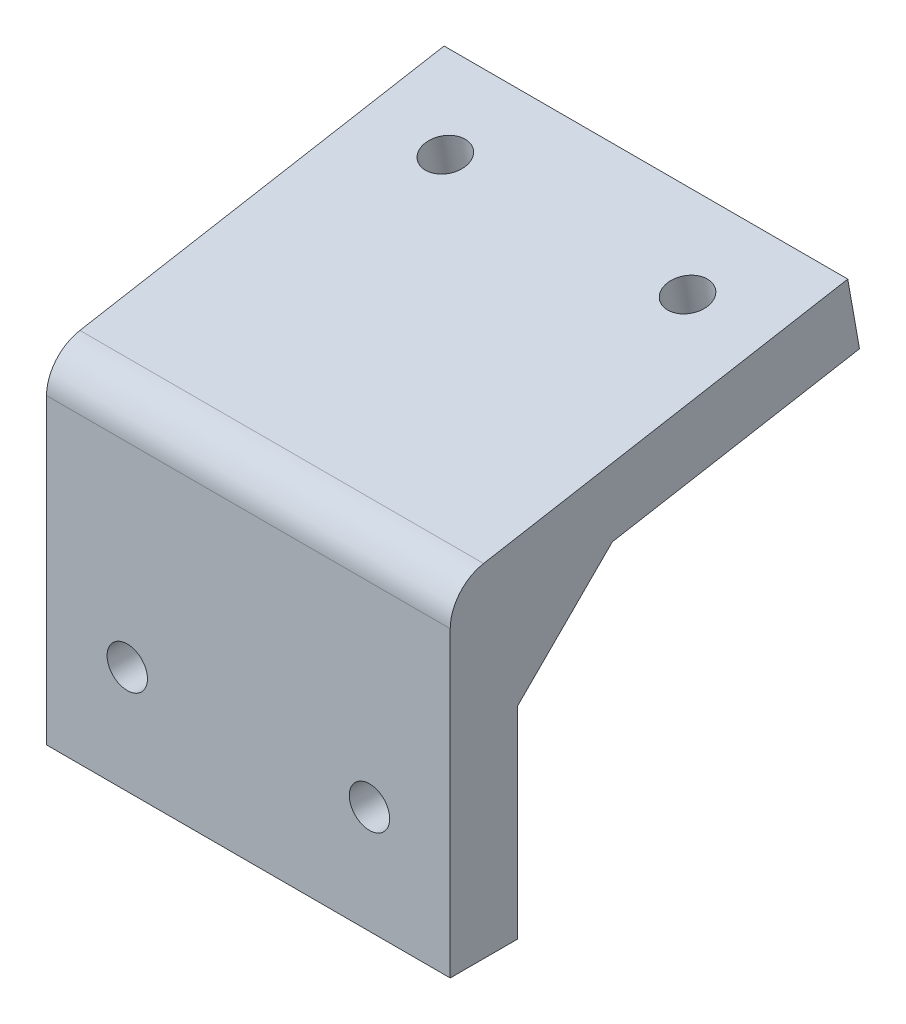
SolidWorks part; units mm, degrees
ref_plane "Front" through (0, 0, 0) normal (0, 0, 1) x (1, 0, 0)
ref_plane "Top" through (0, 0, 0) normal (0, 1, 0) x (1, 0, 0)
ref_plane "Right" through (0, 0, 0) normal (1, 0, 0) x (0, 0, -1)
sketch "草图1" plane through (0, 0, 0) normal (1, 0, 0) x (0, 0, -1)
  line L0 (0, 0) -> (5, 0)
  line L1 (0, 0) -> (0, 25)
  line L2 (0, 25) -> (29.5442, 30.2094)
  line L3 (29.5442, 30.2094) -> (30.4125, 25.2854)
  line L4 (30.4125, 25.2854) -> (5, 20.8045)
  line L5 (5, 20.8045) -> (5, 0)
  dimension "D1" = 5
  dimension "D2" = 25
  dimension "D3" = 30
  dimension "D4" = 5
  dimension "D5" = 100
extrude "凸台-拉伸1" add sketch "草图1" along normal blind 30
fillet "圆角1" radius 3 2 edges at (15, 20.8045, -5) (15, 25, 0)
sketch "草图2" plane through (0, 0, 0) normal (0, 0, 1) x (1, 0, 0)
  line L1 (30, 0) -> (0, 0) construction
  line L2 (0, 22.4827) -> (0, 0) construction
  circle A0 centre (6, 8) radius 1.5
  circle A1 centre (24, 8) radius 1.5
  dimension "D1" = 3
  dimension "D2" = 8
  dimension "D3" = 6
  dimension "D4" = 2
extrude "切除-拉伸1" cut sketch "草图2" against normal through all
sketch "草图3" plane through (0, 24.2462, 4.2753) normal (0, 0.9848, 0.1736) x (1, 0, 0)
  line L0 (30, 34.3412) -> (0, 34.3412) construction
  line L1 (0, 34.3412) -> (0, 6.8585) construction
  circle A0 centre (6, 28.3412) radius 1.5
  circle A1 centre (24, 28.3412) radius 1.5
  dimension "D1" = 3
  dimension "D2" = 3
  dimension "D3" = 6
  dimension "D4" = 6
  dimension "D5" = 18
extrude "切除-拉伸2" cut sketch "草图3" against normal through all
sketch "草图4" plane through (30, 0, 0) normal (1, 0, 0) x (0, 0, -1)
  line L0 (5, 0) -> (5, 18.2872) construction
  line L1 (7.4791, 21.2416) -> (30.4125, 25.2854) construction
  line L2 (5, 15) -> (5, 18.2872)
  line L3 (7.4791, 21.2416) -> (12.0471, 22.0471)
  line L4 (12.0471, 22.0471) -> (5, 15)
  line L5 (0, 0) -> (5, 0) construction
  arc A0 (7.4791, 21.2416) -> (5, 18.2872) centre (8, 18.2872) ccw construction
  arc A1 (7.4791, 21.2416) -> (5, 18.2872) centre (8, 18.2872) ccw
  dimension "D1" = 135
  dimension "D2" = 15
extrude "凸台-拉伸2" add sketch "草图4" against normal up to surface (30 mm away) up to face at (0, 17.9807, -9.8549)
